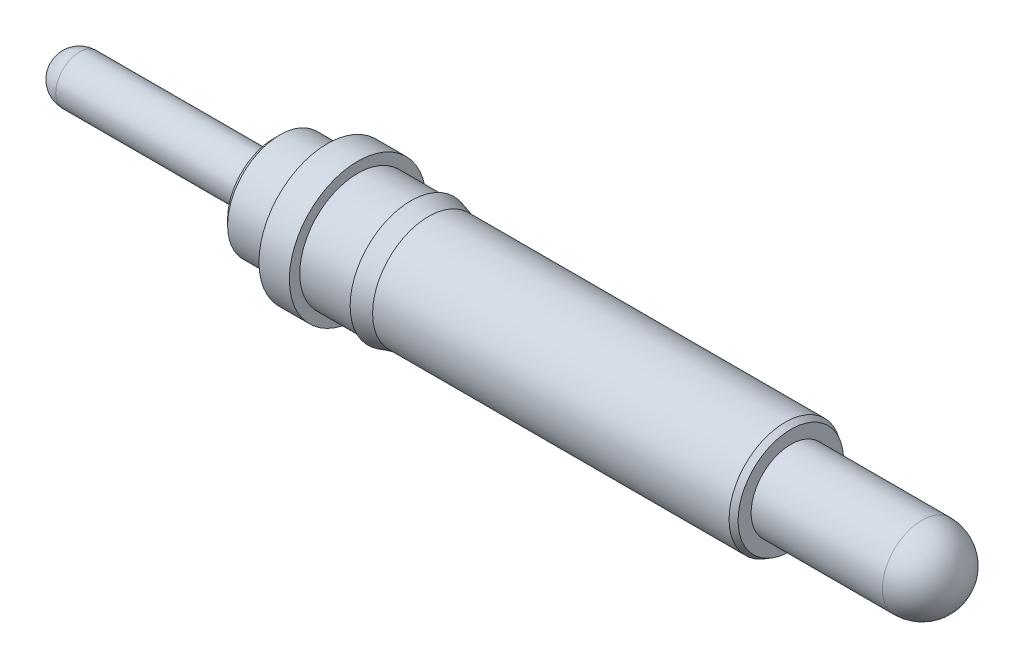
SolidWorks part; units mm, degrees
material "Brass Alloy 385"
ref_plane "Front Plane" through (0, 0, 0) normal (0, 0, 1) x (1, 0, 0)
ref_plane "Top Plane" through (0, 0, 0) normal (0, 1, 0) x (1, 0, 0)
ref_plane "Right Plane" through (0, 0, 0) normal (1, 0, 0) x (0, 0, -1)
sketch "Sketch1" plane through (0, 0, 0) normal (0, 0, 1) x (1, 0, 0)
  line L0 (0, 0) -> (13.8006, 0) construction
  line L1 (0, 0) -> (12.1158, 0)
  line L4 (0.3175, 0.3175) -> (2.921, 0.3175)
  line L5 (2.921, 0.3175) -> (2.921, 0.6223)
  line L6 (2.921, 0.6223) -> (2.9972, 0.6985)
  line L7 (2.9972, 0.6985) -> (3.6322, 0.6985)
  line L8 (3.6322, 0.6985) -> (3.6322, 0.9144)
  line L9 (3.6322, 0.9144) -> (4.0386, 0.9144)
  line L10 (4.0386, 0.9144) -> (4.0386, 0.7747)
  line L11 (4.0386, 0.7747) -> (4.7498, 0.7747)
  line L12 (4.7498, 0.7747) -> (4.7498, 0.8128)
  line L13 (4.7498, 0.8128) -> (4.9868, 0.7493)
  line L14 (4.9868, 0.7493) -> (9.7536, 0.7493)
  line L15 (9.7536, 0.7493) -> (9.8298, 0.7053)
  line L16 (9.8298, 0.7053) -> (9.8298, 0.5309)
  line L17 (9.8298, 0.5309) -> (11.5849, 0.5309)
  arc A0 (12.1158, 0) -> (11.5849, 0.5309) centre (11.5849, 0) ccw
  arc A2 (0.3175, 0.3175) -> (0, 0) centre (0.3175, 0) ccw
  dimension "D1" = 0.3175
  dimension "D14" = 0.5309
  dimension "D2" = 0.635
  dimension "D3" = 1.397
  dimension "D4" = 1.8288
  dimension "D5" = 1.4986
  dimension "D6" = 1.0617
  dimension "D7" = 1.6256
  dimension "D8" = 1.5494
  dimension "D9" = 15
  dimension "D10" = 30
  dimension "D11" = 0.4064
  dimension "D12" = 0.7112
  dimension "D13" = 0.7112
  dimension "B" = 6.9088
  dimension "D15" = 2.921
  dimension "A" = 8.4836
  dimension "D17" = 0.0762
  dimension "D20" = 45
  dimension "D21" = 0.0762
revolve "Revolve1" add sketch "Sketch1" angle 360 about L0
